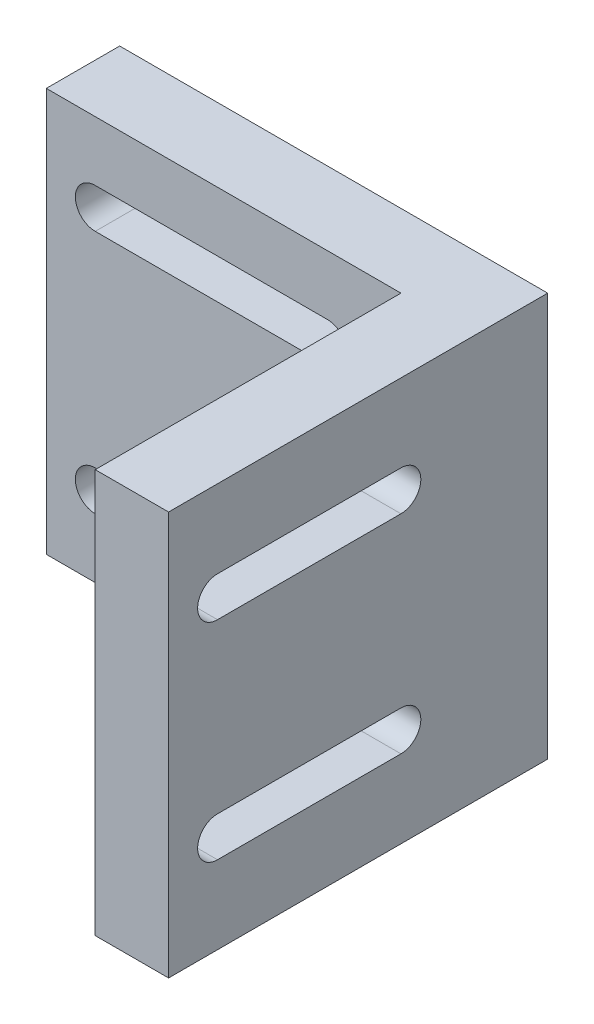
SolidWorks part; units mm, degrees
material "SKD11淬火HRC56-60"
ref_plane "前基準面" through (0, 0, 0) normal (0, 0, 1) x (1, 0, 0)
ref_plane "上基準面" through (0, 0, 0) normal (0, 1, 0) x (1, 0, 0)
ref_plane "右基準面" through (0, 0, 0) normal (1, 0, 0) x (0, 0, -1)
sketch "草图1" plane through (0, 0, 0) normal (0, 0, 1) x (1, 0, 0)
  line L1 (0, 0) -> (70, 0)
  line L2 (0, 0) -> (0, 66)
  line L3 (0, 66) -> (70, 66)
  line L4 (70, 0) -> (70, 66)
  dimension "D1" = 70
  dimension "D2" = 66
extrude "凸台-拉伸1" add sketch "草图1" along normal blind 12
sketch "草图2" plane through (0, 0, 12) normal (0, 0, 1) x (1, 0, 0)
  line L1 (70, 66) -> (0, 66) construction
  line L2 (70, 0) -> (58, 0)
  line L3 (70, 0) -> (70, 66)
  line L4 (70, 66) -> (58, 66)
  line L5 (58, 0) -> (58, 66)
  dimension "D1" = 12
extrude "凸台-拉伸2" add sketch "草图2" along normal blind 50
sketch "草图3" plane through (58, 0, 0) normal (-1, 0, 0) x (0, 0, 1)
  line L0 (24, 16) -> (54, 16) construction
  line L1 (24, 19.25) -> (54, 19.25)
  line L2 (24, 12.75) -> (54, 12.75)
  line L3 (62, 33) -> (15.3113, 33) construction
  line L4 (62, 66) -> (62, 0) construction
  line L5 (24, 50) -> (54, 50) construction
  line L6 (24, 46.75) -> (54, 46.75)
  line L7 (24, 53.25) -> (54, 53.25)
  arc A0 (24, 19.25) -> (24, 12.75) centre (24, 16) ccw
  arc A1 (54, 12.75) -> (54, 19.25) centre (54, 16) ccw
  arc A2 (24, 46.75) -> (24, 53.25) centre (24, 50) cw
  arc A3 (54, 53.25) -> (54, 46.75) centre (54, 50) cw
  point P2 (39, 16)
  point P13 (39, 50)
  dimension "D3" = 8
  dimension "D1" = 6.5
  dimension "D2" = 30
  dimension "D4" = 34
extrude "切除-拉伸1" cut sketch "草图3" against normal blind 40
sketch "草图6" plane through (0, 0, 12) normal (0, 0, 1) x (1, 0, 0)
  line L0 (8, 13) -> (46, 13) construction
  line L1 (8, 16.25) -> (46, 16.25)
  line L2 (8, 9.75) -> (46, 9.75)
  line L3 (0, 33) -> (48.5095, 33) construction
  line L4 (0, 66) -> (0, 0) construction
  line L5 (8, 53) -> (46, 53) construction
  line L6 (8, 49.75) -> (46, 49.75)
  line L7 (8, 56.25) -> (46, 56.25)
  arc A0 (8, 16.25) -> (8, 9.75) centre (8, 13) ccw
  arc A1 (46, 9.75) -> (46, 16.25) centre (46, 13) ccw
  arc A2 (8, 49.75) -> (8, 56.25) centre (8, 53) cw
  arc A3 (46, 56.25) -> (46, 49.75) centre (46, 53) cw
  point P2 (27, 13)
  point P13 (27, 53)
  dimension "D1" = 8
  dimension "D2" = 40
  dimension "D3" = 6.5
  dimension "D4" = 38
extrude "切除-拉伸2" cut sketch "草图6" against normal blind 40
